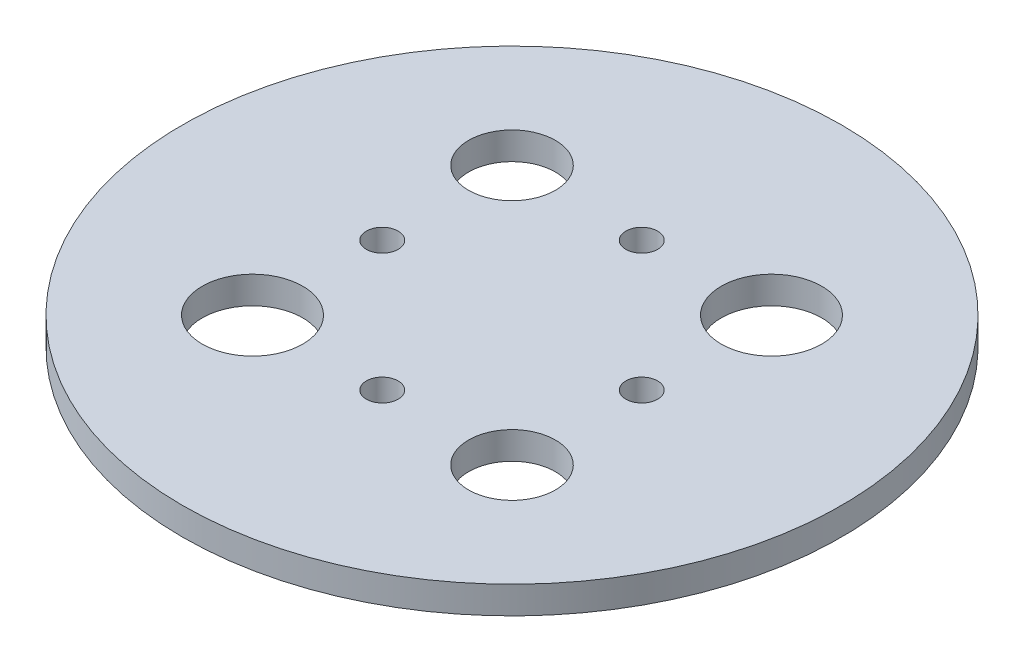
SolidWorks part; units mm, degrees
material "polylactic acid(PLA)(20%)"
ref_plane "Front Plane" through (0, 0, 0) normal (0, 0, 1) x (1, 0, 0)
ref_plane "Top Plane" through (0, 0, 0) normal (0, 1, 0) x (1, 0, 0)
ref_plane "Right Plane" through (0, 0, 0) normal (1, 0, 0) x (0, 0, -1)
sketch "Sketch1" plane through (0, 0, 0) normal (0, 1, 0) x (1, 0, 0)
  line L1 (-50, 50) -> (50, 50)
  line L2 (-50, 50) -> (-50, -50)
  line L3 (-50, -50) -> (50, -50)
  line L4 (50, 50) -> (50, -50)
  circle A0 centre (0, 0) radius 76.2
  point P4 (50, 0)
  point P7 (0, -50)
  dimension "D2" = 152.4
  dimension "D1" = 100
extrude "Boss-Extrude1" add sketch "Sketch1" along normal blind 6.35 contours A0
sketch "Sketch3" plane through (0, 0, 0) normal (0, 1, 0) x (1, 0, 0)
  circle A0 centre (-30, 30) radius 10.025
  circle A1 centre (30, 30) radius 10.025 construction
  circle A2 centre (30, -30) radius 10.025
  circle A3 centre (-30, -30) radius 10.025 construction
  circle A4 centre (-30, 30) radius 19.304 construction
  circle A5 centre (-30, -30) radius 19.304 construction
  circle A6 centre (30, 30) radius 19.304 construction
  circle A7 centre (0, 30) radius 3.675
  circle A8 centre (0, 30) radius 7.5 construction
  circle A9 centre (30, 0) radius 3.675
  circle A10 centre (0, -30) radius 3.675
  circle A11 centre (-30, 0) radius 3.675
  circle A14 centre (30, 30) radius 11.6125
  circle A15 centre (-30, -30) radius 11.6125
  point P14 (0, 0)
  point P29 (0, 0)
  dimension "D1" = 20.05
  dimension "D2" = 38.608
  dimension "D4" = 7.35
  dimension "D5" = 15
  dimension "D7" = 23.225
  dimension "D8" = 60
  dimension "D3" = 4
  dimension "D6" = 4
extrude "Cut-Extrude3" cut sketch "Sketch3" against normal through all and the other way through all
